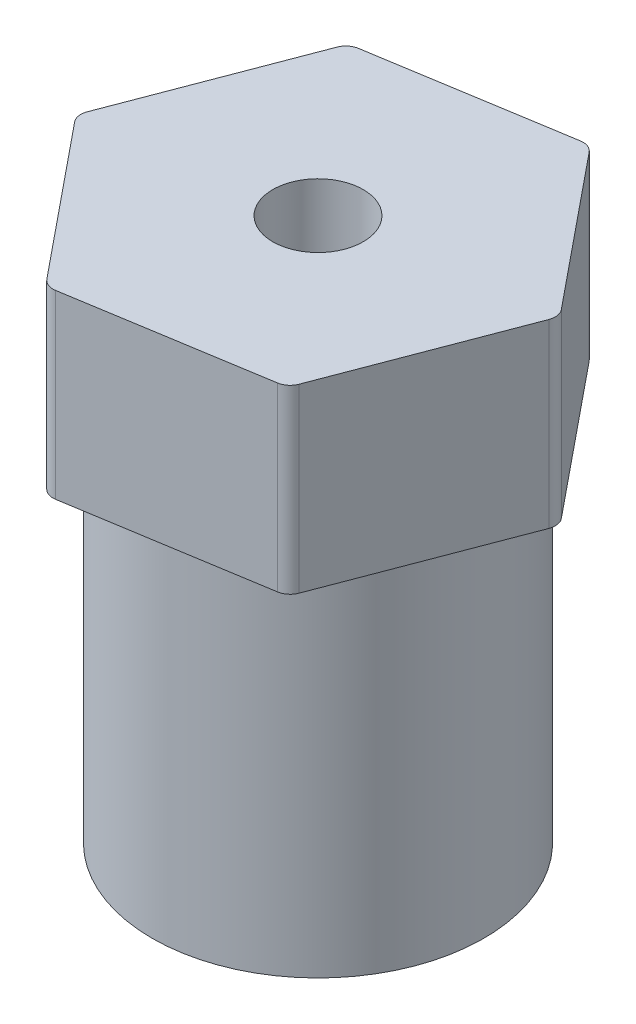
SolidWorks part; units mm, degrees
material "Brass"
ref_plane "Front Plane" through (0, 0, 0) normal (0, 0, 1) x (1, 0, 0)
ref_plane "Top Plane" through (0, 0, 0) normal (0, 1, 0) x (1, 0, 0)
ref_plane "Right Plane" through (0, 0, 0) normal (1, 0, 0) x (0, 0, -1)
sketch "Sketch1" plane through (0, 0, 0) normal (0, 1, 0) x (1, 0, 0)
  circle A0 centre (0, 0) radius 5.5
  dimension "D1" = 11
extrude "Boss-Extrude1" add sketch "Sketch1" along normal blind 12
sketch "Sketch2" plane through (0, 12, 0) normal (0, 1, 0) x (1, 0, 0)
  line L1 (4.4212, -5.4271) -> (6.9106, 1.1153)
  line L2 (6.9106, 1.1153) -> (2.4894, 6.5424)
  line L3 (2.4894, 6.5424) -> (-4.4212, 5.4271)
  line L4 (-4.4212, 5.4271) -> (-6.9106, -1.1153)
  line L5 (-6.9106, -1.1153) -> (-2.4894, -6.5424)
  line L6 (-2.4894, -6.5424) -> (4.4212, -5.4271)
  circle A0 centre (0, 0) radius 6.0622 construction
  dimension "D1" = 14
extrude "Boss-Extrude2" add sketch "Sketch2" along normal blind 6
sketch "Sketch3" plane through (0, 0, 0) normal (0, -1, 0) x (1, 0, 0)
  point P0 (0, 0)
hole_wizard "M5 Clearance Hole1" positions "Sketch3" profile "Sketch4" hole size "M5" standard "ISO"
sketch "Sketch4" plane through (0, 0, 0) normal (1, 0, 0) x (0, 0, -1)
  line L0 (0, 0) -> (0, 13.6524)
  line L1 (0, 13.6524) -> (2.75, 12)
  line L2 (2.75, 12) -> (2.75, 0)
  line L5 (2.75, 0) -> (0, 0)
  line L10 (0, 13.6524) -> (-2.75, 12) construction
  line L11 (0, -6.35) -> (0, 107.95) construction
  dimension "Hole Dia." = 5.5
  dimension "Hole Depth" = 12
  dimension "Drill Angle" = 118
sketch "Sketch5" plane through (0, 18, 0) normal (0, 1, 0) x (1, 0, 0)
  point P0 (0, 0)
hole_wizard "Ø3.0 (3) Diameter Hole1" positions "Sketch5" profile "Sketch6" hole size "Ø3.0" standard "ISO"
sketch "Sketch6" plane through (0, 18, 0) normal (1, 0, 0) x (0, 0, 1)
  line L0 (0, 0) -> (0, 6.9013)
  line L1 (0, 6.9013) -> (1.5, 6)
  line L2 (1.5, 6) -> (1.5, 0)
  line L5 (1.5, 0) -> (0, 0)
  line L10 (0, 6.9013) -> (-1.5, 6) construction
  line L11 (0, -6.35) -> (0, 107.95) construction
  dimension "Hole Dia." = 3
  dimension "Hole Depth" = 6
  dimension "Drill Angle" = 118
fillet "Fillet1" radius 0.5 6 edges at (-4.4212, 15, -5.4271) (2.4894, 15, -6.5424) (6.9106, 15, -1.1153) (4.4212, 15, 5.4271) (-2.4894, 15, 6.5424) (-6.9106, 15, 1.1153)
